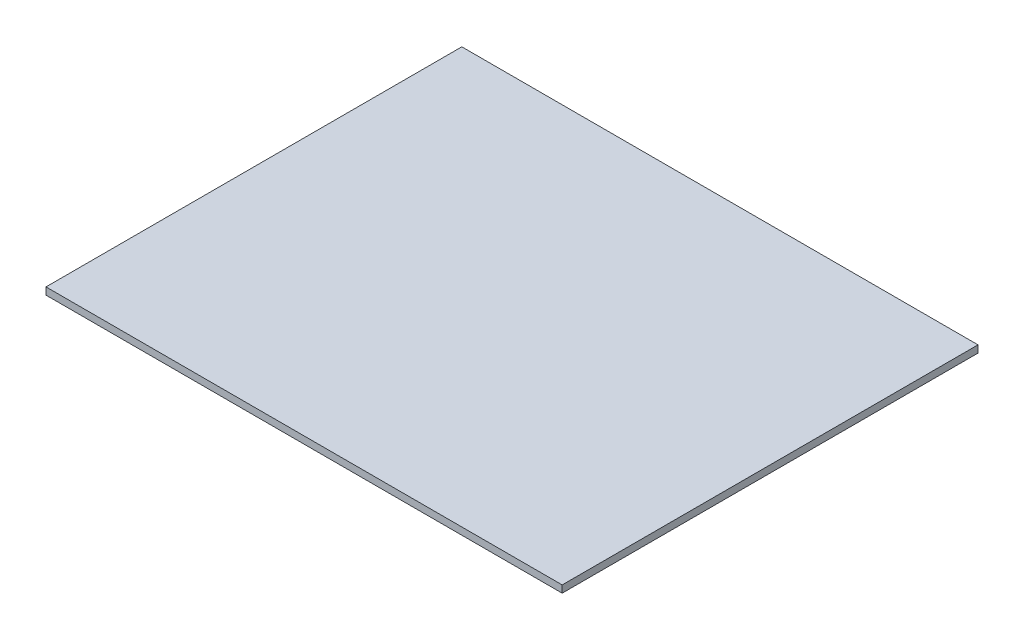
SolidWorks part; units mm, degrees
material "Vidro"
ref_plane "Plano frontal" through (0, 0, 0) normal (0, 0, 1) x (1, 0, 0)
ref_plane "Plano superior" through (0, 0, 0) normal (0, 1, 0) x (1, 0, 0)
ref_plane "Plano direito" through (0, 0, 0) normal (1, 0, 0) x (0, 0, -1)
sketch "Esboço2" plane through (0, 0, 0) normal (0, 1, 0) x (1, 0, 0)
  line L0 (0, 163.8809) -> (0, -163.8809) construction
  line L1 (-197.746, 0) -> (197.746, 0) construction
  line L2 (180, 145) -> (-180, 145)
  line L3 (-180, 145) -> (-180, -145)
  line L4 (180, -145) -> (-180, -145)
  line L5 (180, 145) -> (180, -145)
  point P5 (197.746, 0)
  point P10 (0, -163.8809)
  dimension "D1" = 360
  dimension "D2" = 290
extrude "Ressalto-extrusão2" add sketch "Esboço2" along normal blind 5
